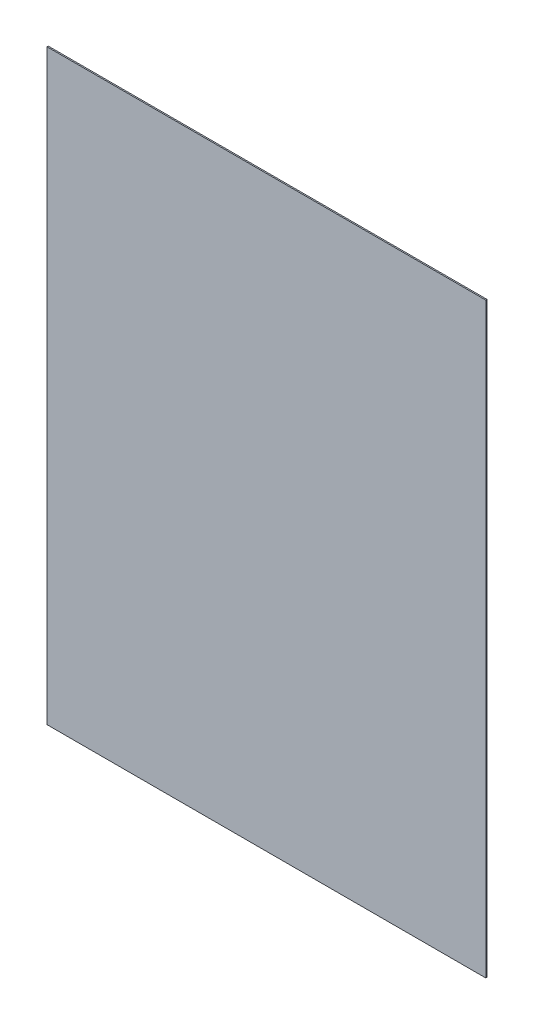
SolidWorks part; units mm, degrees
material "Alloy Steel"
ref_plane "Front Plane" through (0, 0, 0) normal (0, 0, 1) x (1, 0, 0)
ref_plane "Top Plane" through (0, 0, 0) normal (0, 1, 0) x (1, 0, 0)
ref_plane "Right Plane" through (0, 0, 0) normal (1, 0, 0) x (0, 0, -1)
sketch "Sketch1" plane through (0, 0, 0) normal (0, 0, 1) x (1, 0, 0)
  line L1 (-305.0562, 162.5) -> (46.2838, 162.5)
  line L2 (-305.0562, 162.5) -> (-305.0562, -307.5)
  line L3 (-305.0562, -307.5) -> (46.2838, -307.5)
  line L4 (46.2838, 162.5) -> (46.2838, -307.5)
  line L5 (-305.0562, 162.5) -> (46.2838, -307.5) construction
  line L6 (-305.0562, -307.5) -> (46.2838, 162.5) construction
  point P0 (-129.3862, -72.5)
  dimension "D1" = 351.34
  dimension "D2" = 470
extrude "Boss-Extrude1" add sketch "Sketch1" along normal blind 1
